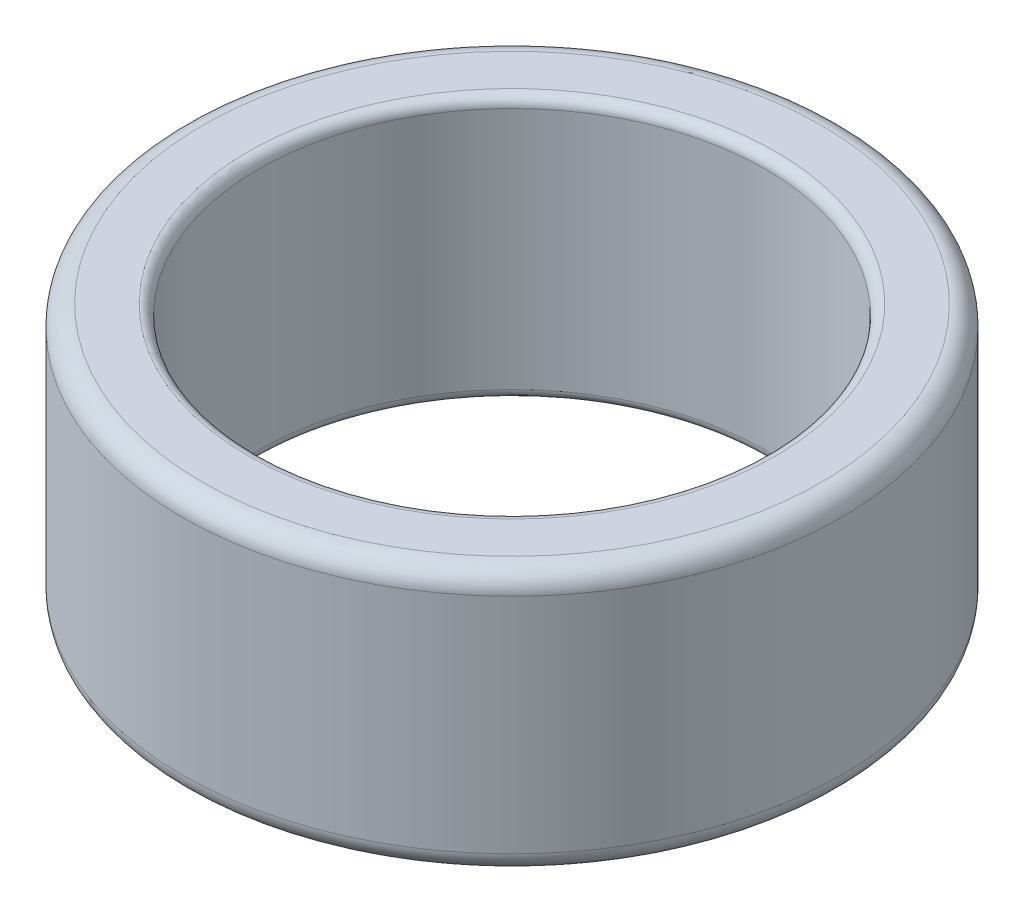
SolidWorks part; units mm, degrees
ref_plane "Спереди" through (0, 0, 0) normal (0, 0, 1) x (1, 0, 0)
ref_plane "Сверху" through (0, 0, 0) normal (0, 1, 0) x (1, 0, 0)
ref_plane "Справа" through (0, 0, 0) normal (1, 0, 0) x (0, 0, -1)
sketch "Эскиз1" plane through (0, 0, 0) normal (0, 1, 0) x (1, 0, 0)
  circle A0 centre (0, 0) radius 32.5
  circle A1 centre (0, 0) radius 25
  dimension "D1" = 65
  dimension "D2" = 50
extrude "Бобышка-Вытянуть1" add sketch "Эскиз1" along normal blind 26
fillet "Скругление1" radius 2 2 edges at (0, 0, 32.5) (0, 26, 32.5)
fillet "Скругление2" radius 1 2 edges at (0, 0, 25) (0, 26, 25)
sketch "Эскиз2" plane through (0, 0, 0) normal (0, -1, 0) x (1, 0, 0)
  text T0 "260/40/19                                   YOKOHAMA                                RC34"
extrude "Бобышка-Вытянуть2" add sketch "Эскиз2" along normal blind 0.1
